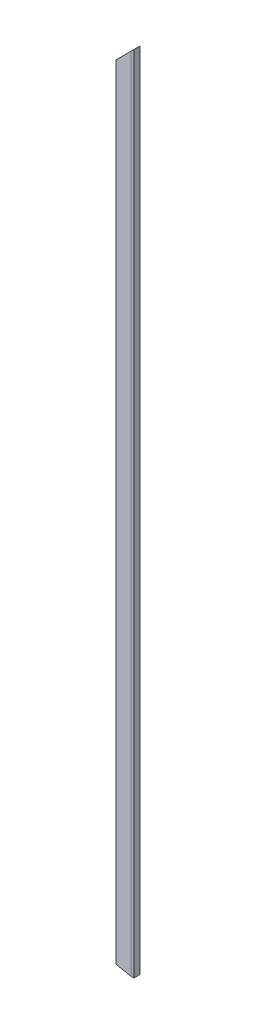
SolidWorks part; units mm, degrees
material "Pine"
ref_plane "Front Plane" through (0, 0, 0) normal (0, 0, 1) x (1, 0, 0)
ref_plane "Top Plane" through (0, 0, 0) normal (0, 1, 0) x (1, 0, 0)
ref_plane "Right Plane" through (0, 0, 0) normal (1, 0, 0) x (0, 0, -1)
sketch "Sketch1" plane through (0, 0, 0) normal (0, 1, 0) x (1, 0, 0)
  line L0 (0, 0) -> (53.975, 0)
  line L1 (53.975, 0) -> (53.975, -15.875)
  line L2 (53.975, -15.875) -> (46.355, -15.875)
  line L3 (46.355, -15.875) -> (0, -8.255)
  line L4 (0, -8.255) -> (0, 0)
  dimension "D1" = 53.975
  dimension "D2" = 15.875
  dimension "D3" = 8.255
  dimension "D4" = 7.62
extrude "Boss-Extrude1" add sketch "Sketch1" along normal blind 2092.325
sketch "Sketch2" plane through (0, 0, 15.875) normal (0, 0, 1) x (1, 0, 0)
  line L0 (53.975, 2092.325) -> (0, 2038.35)
  line L1 (0, 2092.325) -> (0, 0) construction
  line L2 (0, 2038.35) -> (0, 2092.325)
  line L3 (0, 2092.325) -> (53.975, 2092.325)
  dimension "D1" = 45
extrude "Cut-Extrude1" cut sketch "Sketch2" against normal through all
sketch "Sketch3" [suppressed] plane through (0, 0, 15.875) normal (0, 0, 1) x (1, 0, 0)
  line L0 (53.975, 0) -> (0, 53.975)
  line L1 (0, 676.275) -> (0, 0) construction
  line L2 (0, 53.975) -> (0, 0)
  line L3 (0, 0) -> (53.975, 0)
  dimension "D1" = 45
extrude "Cut-Extrude2" [suppressed] cut sketch "Sketch3" against normal through all
